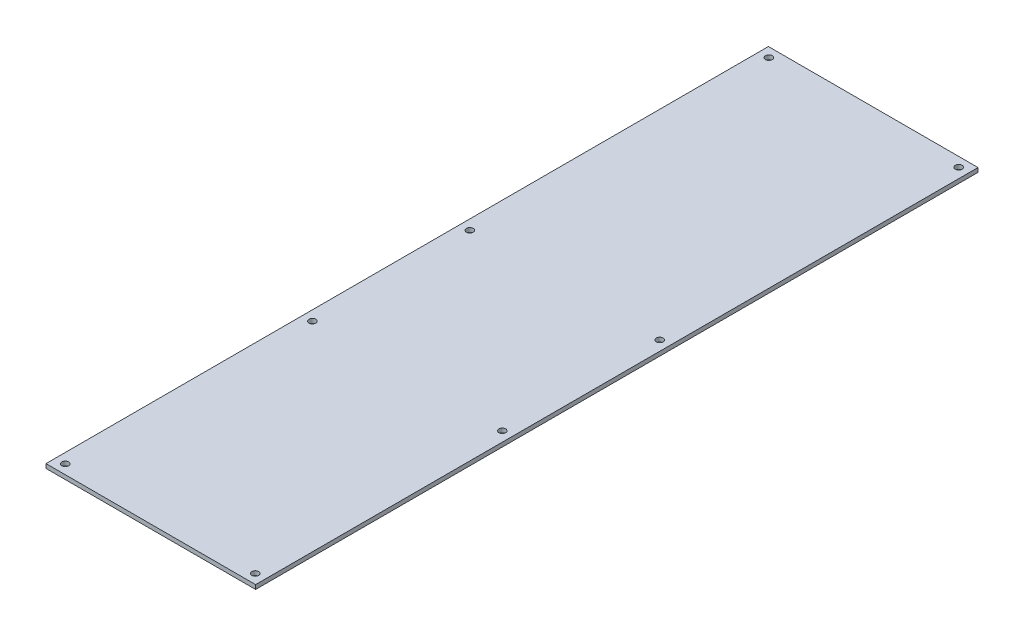
SolidWorks part; units mm, degrees
material "PCB Multi Layer"
ref_plane "Front Plane" through (0, 0, 0) normal (0, 0, 1) x (1, 0, 0)
ref_plane "Top Plane" through (0, 0, 0) normal (0, 1, 0) x (1, 0, 0)
ref_plane "Right Plane" through (0, 0, 0) normal (1, 0, 0) x (0, 0, -1)
sketch "Sketch1" plane through (0, 0, 0) normal (0, 1, 0) x (1, 0, 0)
  line L1 (0, 0) -> (89.225, 0)
  line L2 (0, 0) -> (0, -307.5)
  line L3 (0, -307.5) -> (89.225, -307.5)
  line L4 (89.225, 0) -> (89.225, -307.5)
  dimension "D1" = 89.225
  dimension "D2" = 307.5
extrude "Boss-Extrude1" add sketch "Sketch1" along normal blind 1.8
hole_wizard "M2.5 Clearance Hole1" positions "Sketch3" profile "Sketch4" hole size "M2.5" standard "ANSI Metric" end condition through all
sketch "Sketch3" plane through (0, 1.8, 0) normal (0, 1, 0) x (1, 0, 0)
  line L0 (0, 0) -> (0, -307.5) construction
  line L1 (89.225, -307.5) -> (89.225, 0) construction
  line L2 (89.225, 0) -> (0, 0) construction
  line L3 (0, -307.5) -> (89.225, -307.5) construction
  point P0 (4.2, -4)
  point P2 (85.025, -4)
  point P4 (85.025, -131.3)
  point P6 (85.025, -198.3)
  point P8 (85.025, -303.5)
  point P10 (4.2, -303.5)
  point P12 (4.2, -198.3)
  point P14 (4.2, -131.3)
  dimension "D1" = 4.2
  dimension "D2" = 4.2
  dimension "D3" = 4
  dimension "D4" = 4
  dimension "D5" = 105.2
  dimension "D6" = 67
sketch "Sketch4" plane through (4.2, 1.8, 4) normal (1, 0, 0) x (0, 0, 1)
  line L0 (0, 0) -> (0, 1.8)
  line L1 (0, 1.8) -> (1.45, 1.8)
  line L2 (1.45, 1.8) -> (1.45, 0)
  line L5 (1.45, 0) -> (0, 0)
  line L11 (0, -6.35) -> (0, 107.95) construction
  dimension "Thru Hole Dia." = 2.9
  dimension "Thru Hole Depth" = 1.8
